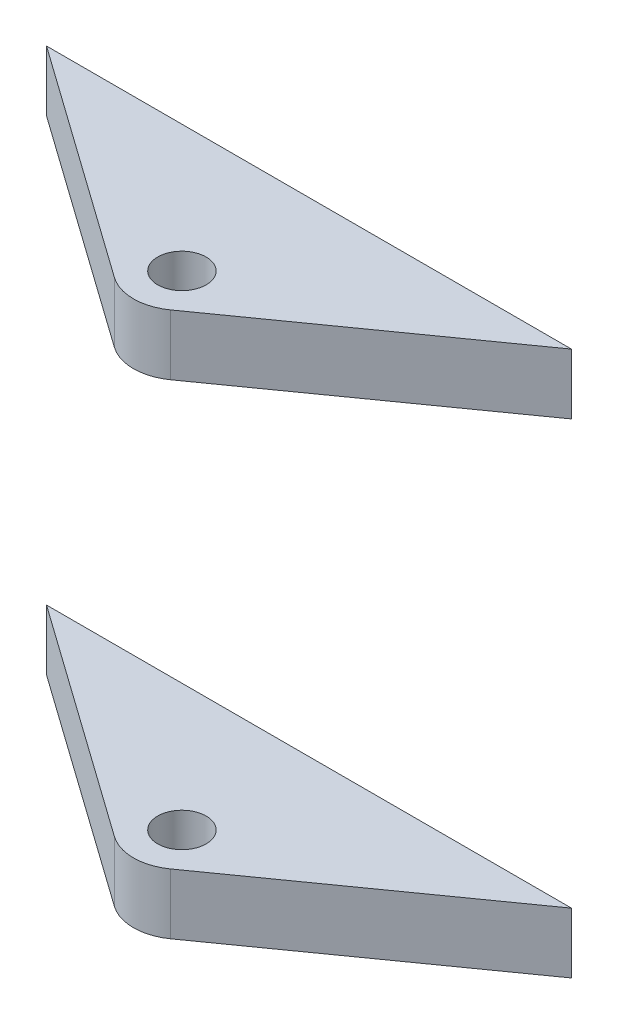
SolidWorks part; units mm, degrees
ref_plane "Front Plane" through (0, 0, 0) normal (0, 0, 1) x (1, 0, 0)
ref_plane "Top Plane" through (0, 0, 0) normal (0, 1, 0) x (1, 0, 0)
ref_plane "Right Plane" through (0, 0, 0) normal (1, 0, 0) x (0, 0, -1)
sketch "Sketch2" plane through (0, 0, 0) normal (0, 0, 1) x (1, 0, 0)
  line L1 (-36.221, 39.7223) -> (50.5257, 39.7223)
  line L2 (-36.221, 39.7223) -> (-36.221, 29.7223)
  line L3 (-36.221, 29.7223) -> (50.5257, 29.7223)
  line L4 (50.5257, 39.7223) -> (50.5257, 29.7223)
  line L5 (-36.221, -50.2777) -> (50.5257, -50.2777)
  line L6 (-36.221, -50.2777) -> (-36.221, -40.2777)
  line L7 (-36.221, -40.2777) -> (50.5257, -40.2777)
  line L8 (50.5257, -50.2777) -> (50.5257, -40.2777)
  circle A0 centre (7.1523, -5.2777) radius 62.5 construction
  point P11 (0, 0)
  point P12 (47.1124, 21.92)
  point P13 (0, 0)
  point P14 (0, 0)
  dimension "D1" = 125
  dimension "D2" = 10
  dimension "D3" = 90
extrude "Boss-Extrude1" add sketch "Sketch2" along normal blind 50
sketch "Sketch3" plane through (0, 39.7223, 0) normal (0, 1, 0) x (1, 0, 0)
  line L0 (50.5257, 0) -> (-36.221, 0)
  line L1 (-36.221, 0) -> (2.5192, -27.5218)
  line L2 (2.5192, -27.5218) -> (11.7855, -27.5218)
  line L3 (11.7855, -27.5218) -> (50.5257, 0)
  line L4 (2.5192, -27.5218) -> (2.5192, 0) construction
  line L5 (11.7855, -27.5218) -> (11.7855, 0) construction
  line L6 (11.7855, -27.5218) -> (2.5192, 0) construction
  line L7 (50.5257, -50) -> (-36.221, -50) construction
  line L8 (-36.221, 0) -> (-36.221, -50)
  line L9 (-36.221, -50) -> (50.5257, -50)
  line L10 (50.5257, -50) -> (50.5257, 0)
  circle A0 centre (7.1523, -21) radius 4
  circle A1 centre (7.1523, -21) radius 8
  point P11 (7.1523, -50)
  point P12 (7.1523, -13.7609)
  line M10 (-36.221, 0) -> (-36.221, -50)
  line M11 (-36.221, -50) -> (50.5257, -50)
  line M12 (50.5257, -50) -> (50.5257, 0)
  dimension "D1" = 21
  dimension "D2" = 8
  dimension "D3" = 4
extrude "Cut-Extrude1" cut sketch "Sketch3" against normal through all both and the other way through all contours A1 L1 L3 M10 M11 M12 | A0
